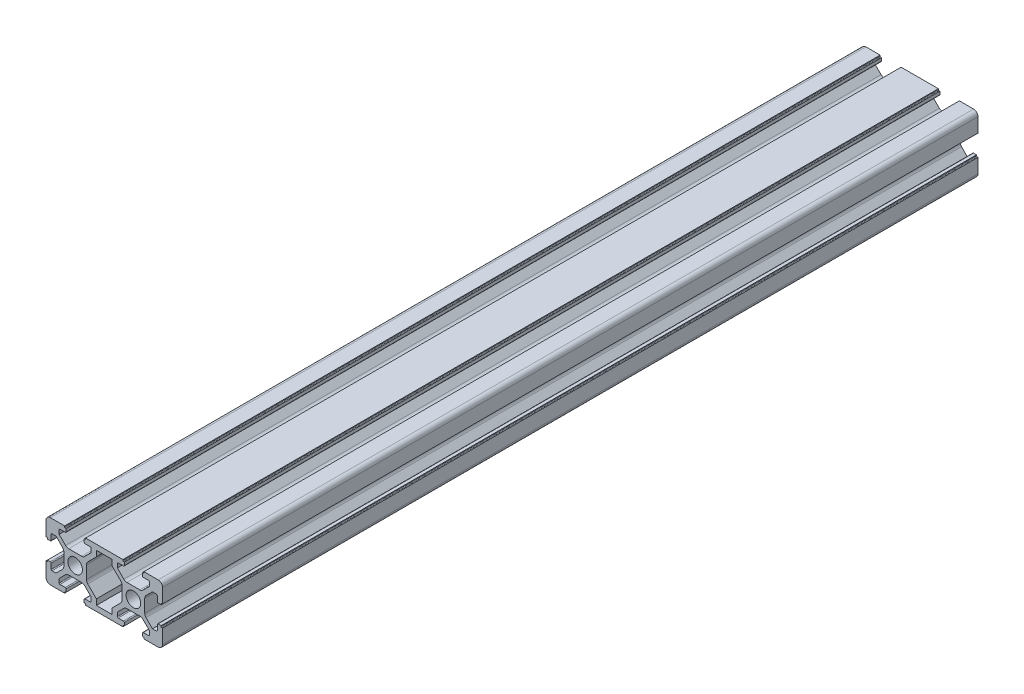
SolidWorks part; units mm, degrees
ref_plane "前视基准面" through (0, 0, 0) normal (0, 0, 1) x (1, 0, 0)
ref_plane "上视基准面" through (0, 0, 0) normal (0, 1, 0) x (1, 0, 0)
ref_plane "右视基准面" through (0, 0, 0) normal (1, 0, 0) x (0, 0, -1)
sketch "草图1" plane through (0, 0, 0) normal (0, 0, 1) x (1, 0, 0)
  line L0 (-1.9716, -6.6942) -> (-4.9322, -3.7335)
  line L1 (-5.3716, -2.6729) -> (-5.3716, 1.7645)
  line L2 (-4.9322, 2.8251) -> (-1.9716, 5.7858)
  line L3 (-0.7716, 9.5458) -> (-5.6716, 9.5458)
  line L4 (-5.6716, 9.5458) -> (-5.6716, 9.2458)
  line L5 (-5.8716, 9.0458) -> (-6.1716, 9.0458)
  line L6 (-6.1716, 9.0458) -> (-6.1716, 8.0458)
  line L7 (-5.8716, 7.7458) -> (-4.0716, 7.7458)
  line L8 (-3.7716, 7.4458) -> (-3.7716, 6.1058)
  line L9 (-3.7716, 6.1058) -> (-5.9922, 3.8851)
  line L10 (-7.0529, 3.4458) -> (-11.4903, 3.4458)
  line L11 (-12.5509, 3.8851) -> (-14.7716, 6.1058)
  line L12 (-14.7716, 6.1058) -> (-14.7716, 7.4458)
  line L13 (-14.4716, 7.7458) -> (-12.6716, 7.7458)
  line L14 (-12.3716, 8.0458) -> (-12.3716, 9.0458)
  line L15 (-12.3716, 9.0458) -> (-12.6716, 9.0458)
  line L16 (-12.8716, 9.2458) -> (-12.8716, 9.5458)
  line L17 (-12.8716, 9.5458) -> (-17.7716, 9.5458)
  line L18 (-19.2716, 8.0458) -> (-19.2716, 3.1458)
  line L19 (-19.2716, 3.1458) -> (-18.9716, 3.1458)
  line L20 (-18.7716, 2.9458) -> (-18.7716, 2.6458)
  line L21 (-18.7716, 2.6458) -> (-17.7716, 2.6458)
  line L22 (-17.4716, 2.9458) -> (-17.4716, 4.7458)
  line L23 (-17.1716, 5.0458) -> (-15.8316, 5.0458)
  line L24 (-15.8316, 5.0458) -> (-13.6109, 2.8251)
  line L25 (-13.1716, 1.7645) -> (-13.1716, -2.6729)
  line L26 (-13.6109, -3.7335) -> (-15.8316, -5.9542)
  line L27 (-15.8316, -5.9542) -> (-17.1716, -5.9542)
  line L28 (-17.4716, -5.6542) -> (-17.4716, -3.8542)
  line L29 (-17.7716, -3.5542) -> (-18.7716, -3.5542)
  line L30 (-18.7716, -3.5542) -> (-18.7716, -3.8542)
  line L31 (-18.9716, -4.0542) -> (-19.2716, -4.0542)
  line L32 (-19.2716, -4.0542) -> (-19.2716, -8.9542)
  line L33 (-17.7716, -10.4542) -> (-12.8716, -10.4542)
  line L34 (-12.8716, -10.4542) -> (-12.8716, -10.1542)
  line L35 (-12.6716, -9.9542) -> (-12.3716, -9.9542)
  line L36 (-12.3716, -9.9542) -> (-12.3716, -8.9542)
  line L37 (-12.6716, -8.6542) -> (-14.4716, -8.6542)
  line L38 (-14.7716, -8.3542) -> (-14.7716, -7.0142)
  line L39 (-14.7716, -7.0142) -> (-12.5509, -4.7935)
  line L40 (-11.4903, -4.3542) -> (-7.0529, -4.3542)
  line L41 (-5.9922, -4.7935) -> (-3.7716, -7.0142)
  line L42 (-3.7716, -7.0142) -> (-3.7716, -8.3542)
  line L43 (-4.0716, -8.6542) -> (-5.8716, -8.6542)
  line L44 (-6.1716, -8.9542) -> (-6.1716, -9.9542)
  line L45 (-6.1716, -9.9542) -> (-5.8716, -9.9542)
  line L46 (-5.6716, -10.1542) -> (-5.6716, -10.4542)
  line L47 (-5.6716, -10.4542) -> (-0.7716, -10.4542)
  line L48 (-0.7716, -10.4542) -> (7.1284, -10.4542)
  line L49 (7.1284, -10.4542) -> (7.1284, -10.1542)
  line L50 (7.3284, -9.9542) -> (7.6284, -9.9542)
  line L51 (7.6284, -9.9542) -> (7.6284, -8.9542)
  line L52 (7.3284, -8.6542) -> (5.5284, -8.6542)
  line L53 (5.2284, -8.3542) -> (5.2284, -7.0142)
  line L54 (5.2284, -7.0142) -> (7.4491, -4.7935)
  line L55 (8.5097, -4.3542) -> (12.9471, -4.3542)
  line L56 (14.0078, -4.7935) -> (16.2284, -7.0142)
  line L57 (16.2284, -7.0142) -> (16.2284, -8.3542)
  line L58 (15.9284, -8.6542) -> (14.1284, -8.6542)
  line L59 (13.8284, -8.9542) -> (13.8284, -9.9542)
  line L60 (13.8284, -9.9542) -> (14.1284, -9.9542)
  line L61 (14.3284, -10.1542) -> (14.3284, -10.4542)
  line L62 (14.3284, -10.4542) -> (19.2284, -10.4542)
  line L63 (20.7284, -8.9542) -> (20.7284, -4.0542)
  line L64 (20.7284, -4.0542) -> (20.4284, -4.0542)
  line L65 (20.2284, -3.8542) -> (20.2284, -3.5542)
  line L66 (20.2284, -3.5542) -> (19.2284, -3.5542)
  line L67 (18.9284, -3.8542) -> (18.9284, -5.6542)
  line L68 (18.6284, -5.9542) -> (17.2884, -5.9542)
  line L69 (17.2884, -5.9542) -> (15.0678, -3.7335)
  line L70 (14.6284, -2.6729) -> (14.6284, 1.7645)
  line L71 (15.0678, 2.8251) -> (17.2884, 5.0458)
  line L72 (17.2884, 5.0458) -> (18.6284, 5.0458)
  line L73 (18.9284, 4.7458) -> (18.9284, 2.9458)
  line L74 (19.2284, 2.6458) -> (20.2284, 2.6458)
  line L75 (20.2284, 2.6458) -> (20.2284, 2.9458)
  line L76 (20.4284, 3.1458) -> (20.7284, 3.1458)
  line L77 (20.7284, 3.1458) -> (20.7284, 8.0458)
  line L78 (19.2284, 9.5458) -> (14.3284, 9.5458)
  line L79 (14.3284, 9.5458) -> (14.3284, 9.2458)
  line L80 (14.1284, 9.0458) -> (13.8284, 9.0458)
  line L81 (13.8284, 9.0458) -> (13.8284, 8.0458)
  line L82 (14.1284, 7.7458) -> (15.9284, 7.7458)
  line L83 (16.2284, 7.4458) -> (16.2284, 6.1058)
  line L84 (16.2284, 6.1058) -> (14.0078, 3.8851)
  line L85 (12.9471, 3.4458) -> (8.5097, 3.4458)
  line L86 (7.4491, 3.8851) -> (5.2284, 6.1058)
  line L87 (5.2284, 6.1058) -> (5.2284, 7.4458)
  line L88 (5.5284, 7.7458) -> (7.3284, 7.7458)
  line L89 (7.6284, 8.0458) -> (7.6284, 9.0458)
  line L90 (7.6284, 9.0458) -> (7.3284, 9.0458)
  line L91 (7.1284, 9.2458) -> (7.1284, 9.5458)
  line L92 (7.1284, 9.5458) -> (2.2284, 9.5458)
  line L93 (3.4284, 5.7858) -> (6.3891, 2.8251)
  line L94 (6.8284, 1.7645) -> (6.8284, -2.6729)
  line L95 (6.3891, -3.7335) -> (3.4284, -6.6942)
  line L96 (-0.7716, 9.5458) -> (2.2284, 9.5458)
  line L99 (-1.9716, 7.7458) -> (3.4284, 7.7458)
  line L100 (3.4284, 7.7458) -> (3.4284, 5.7858)
  line L101 (-1.9716, 7.7458) -> (-1.9716, 5.7858)
  line L102 (-1.9716, -8.6542) -> (3.4284, -8.6542)
  line L103 (3.4284, -8.6542) -> (3.4284, -6.6942)
  line L104 (-1.9716, -8.6542) -> (-1.9716, -6.6942)
  arc A1 (-5.3716, -2.6729) -> (-4.9322, -3.7335) centre (-3.8716, -2.6729) ccw
  arc A2 (-4.9322, 2.8251) -> (-5.3716, 1.7645) centre (-3.8716, 1.7645) ccw
  arc A3 (-5.8716, 9.0458) -> (-5.6716, 9.2458) centre (-5.8716, 9.2458) ccw
  arc A4 (-6.1716, 8.0458) -> (-5.8716, 7.7458) centre (-5.8716, 8.0458) ccw
  arc A5 (-3.7716, 7.4458) -> (-4.0716, 7.7458) centre (-4.0716, 7.4458) ccw
  arc A6 (-7.0529, 3.4458) -> (-5.9922, 3.8851) centre (-7.0529, 4.9458) ccw
  arc A7 (-12.5509, 3.8851) -> (-11.4903, 3.4458) centre (-11.4903, 4.9458) ccw
  arc A8 (-14.4716, 7.7458) -> (-14.7716, 7.4458) centre (-14.4716, 7.4458) ccw
  arc A9 (-12.6716, 7.7458) -> (-12.3716, 8.0458) centre (-12.6716, 8.0458) ccw
  arc A10 (-12.8716, 9.2458) -> (-12.6716, 9.0458) centre (-12.6716, 9.2458) ccw
  arc A11 (-17.7716, 9.5458) -> (-19.2716, 8.0458) centre (-17.7716, 8.0458) ccw
  arc A12 (-18.7716, 2.9458) -> (-18.9716, 3.1458) centre (-18.9716, 2.9458) ccw
  arc A13 (-17.7716, 2.6458) -> (-17.4716, 2.9458) centre (-17.7716, 2.9458) ccw
  arc A14 (-17.1716, 5.0458) -> (-17.4716, 4.7458) centre (-17.1716, 4.7458) ccw
  arc A15 (-13.1716, 1.7645) -> (-13.6109, 2.8251) centre (-14.6716, 1.7645) ccw
  arc A16 (-13.6109, -3.7335) -> (-13.1716, -2.6729) centre (-14.6716, -2.6729) ccw
  arc A17 (-17.4716, -5.6542) -> (-17.1716, -5.9542) centre (-17.1716, -5.6542) ccw
  arc A18 (-17.4716, -3.8542) -> (-17.7716, -3.5542) centre (-17.7716, -3.8542) ccw
  arc A19 (-18.9716, -4.0542) -> (-18.7716, -3.8542) centre (-18.9716, -3.8542) ccw
  arc A20 (-19.2716, -8.9542) -> (-17.7716, -10.4542) centre (-17.7716, -8.9542) ccw
  arc A21 (-12.6716, -9.9542) -> (-12.8716, -10.1542) centre (-12.6716, -10.1542) ccw
  arc A22 (-12.3716, -8.9542) -> (-12.6716, -8.6542) centre (-12.6716, -8.9542) ccw
  arc A23 (-14.7716, -8.3542) -> (-14.4716, -8.6542) centre (-14.4716, -8.3542) ccw
  arc A24 (-11.4903, -4.3542) -> (-12.5509, -4.7935) centre (-11.4903, -5.8542) ccw
  arc A25 (-5.9922, -4.7935) -> (-7.0529, -4.3542) centre (-7.0529, -5.8542) ccw
  arc A26 (-4.0716, -8.6542) -> (-3.7716, -8.3542) centre (-4.0716, -8.3542) ccw
  arc A27 (-5.8716, -8.6542) -> (-6.1716, -8.9542) centre (-5.8716, -8.9542) ccw
  arc A28 (-5.6716, -10.1542) -> (-5.8716, -9.9542) centre (-5.8716, -10.1542) ccw
  arc A29 (7.3284, -9.9542) -> (7.1284, -10.1542) centre (7.3284, -10.1542) ccw
  arc A30 (7.6284, -8.9542) -> (7.3284, -8.6542) centre (7.3284, -8.9542) ccw
  arc A31 (5.2284, -8.3542) -> (5.5284, -8.6542) centre (5.5284, -8.3542) ccw
  arc A32 (8.5097, -4.3542) -> (7.4491, -4.7935) centre (8.5097, -5.8542) ccw
  arc A33 (14.0078, -4.7935) -> (12.9471, -4.3542) centre (12.9471, -5.8542) ccw
  arc A34 (15.9284, -8.6542) -> (16.2284, -8.3542) centre (15.9284, -8.3542) ccw
  arc A35 (14.1284, -8.6542) -> (13.8284, -8.9542) centre (14.1284, -8.9542) ccw
  arc A36 (14.3284, -10.1542) -> (14.1284, -9.9542) centre (14.1284, -10.1542) ccw
  arc A37 (19.2284, -10.4542) -> (20.7284, -8.9542) centre (19.2284, -8.9542) ccw
  arc A38 (20.2284, -3.8542) -> (20.4284, -4.0542) centre (20.4284, -3.8542) ccw
  arc A39 (19.2284, -3.5542) -> (18.9284, -3.8542) centre (19.2284, -3.8542) ccw
  arc A40 (18.6284, -5.9542) -> (18.9284, -5.6542) centre (18.6284, -5.6542) ccw
  arc A41 (14.6284, -2.6729) -> (15.0678, -3.7335) centre (16.1284, -2.6729) ccw
  arc A42 (15.0678, 2.8251) -> (14.6284, 1.7645) centre (16.1284, 1.7645) ccw
  arc A43 (18.9284, 4.7458) -> (18.6284, 5.0458) centre (18.6284, 4.7458) ccw
  arc A44 (18.9284, 2.9458) -> (19.2284, 2.6458) centre (19.2284, 2.9458) ccw
  arc A45 (20.4284, 3.1458) -> (20.2284, 2.9458) centre (20.4284, 2.9458) ccw
  arc A46 (20.7284, 8.0458) -> (19.2284, 9.5458) centre (19.2284, 8.0458) ccw
  arc A47 (14.1284, 9.0458) -> (14.3284, 9.2458) centre (14.1284, 9.2458) ccw
  arc A48 (13.8284, 8.0458) -> (14.1284, 7.7458) centre (14.1284, 8.0458) ccw
  arc A49 (16.2284, 7.4458) -> (15.9284, 7.7458) centre (15.9284, 7.4458) ccw
  arc A50 (12.9471, 3.4458) -> (14.0078, 3.8851) centre (12.9471, 4.9458) ccw
  arc A51 (7.4491, 3.8851) -> (8.5097, 3.4458) centre (8.5097, 4.9458) ccw
  arc A52 (5.5284, 7.7458) -> (5.2284, 7.4458) centre (5.5284, 7.4458) ccw
  arc A53 (7.3284, 7.7458) -> (7.6284, 8.0458) centre (7.3284, 8.0458) ccw
  arc A54 (7.1284, 9.2458) -> (7.3284, 9.0458) centre (7.3284, 9.2458) ccw
  arc A55 (6.8284, 1.7645) -> (6.3891, 2.8251) centre (5.3284, 1.7645) ccw
  arc A56 (6.3891, -3.7335) -> (6.8284, -2.6729) centre (5.3284, -2.6729) ccw
  circle A58 centre (10.7284, -0.4542) radius 2.5
  circle A63 centre (-9.2716, -0.4542) radius 2.5
extrude "凸台-拉伸1" add sketch "草图1" along normal blind 280
